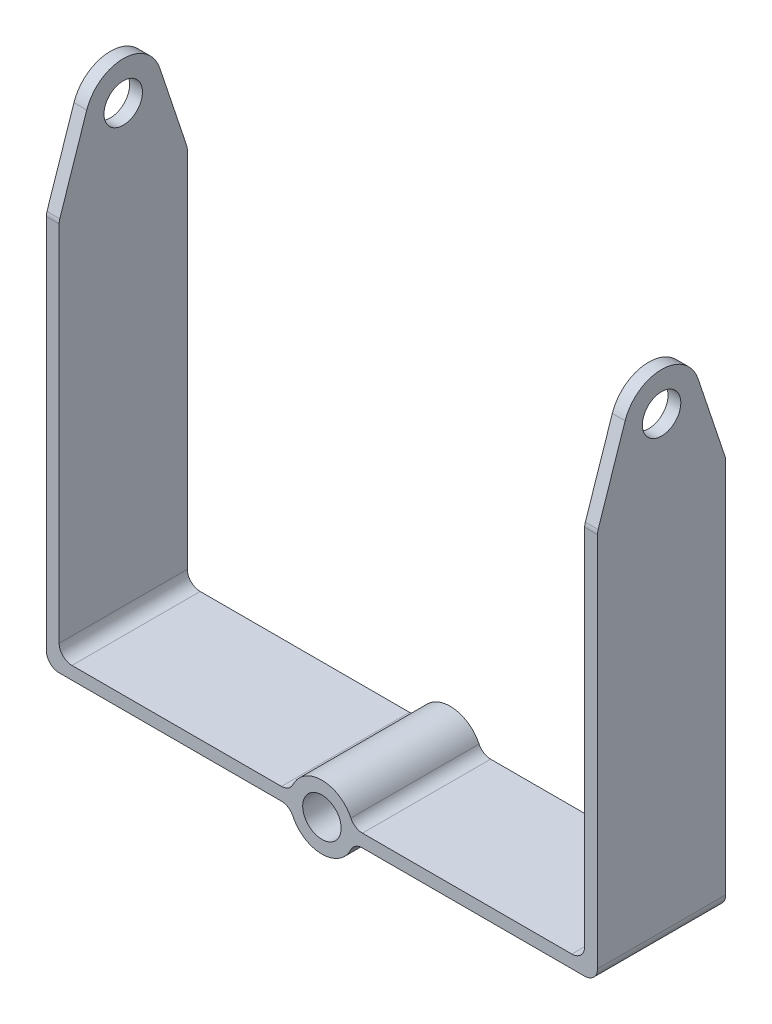
SolidWorks part; units mm, degrees
ref_plane "Plan de face" through (0, 0, 0) normal (0, 0, 1) x (1, 0, 0)
ref_plane "Plan de dessus" through (0, 0, 0) normal (0, 1, 0) x (1, 0, 0)
ref_plane "Plan de droite" through (0, 0, 0) normal (1, 0, 0) x (0, 0, -1)
sketch "Esquisse1" plane through (0, 0, 0) normal (0, 0, 1) x (1, 0, 0)
  line L0 (0, 0) -> (0, 390)
  line L1 (0, 390) -> (10, 390)
  line L2 (10, 390) -> (10, 10)
  line L3 (10, 10) -> (420, 10) construction
  line L4 (420, 10) -> (420, 390)
  line L5 (420, 390) -> (430, 390)
  line L6 (430, 390) -> (430, 0)
  line L7 (0, 0) -> (10, 0)
  line L8 (10, 390) -> (420, 390) construction
  line L9 (420, 10) -> (420, 0) construction
  line L10 (10, 10) -> (10, 0) construction
  line L11 (430, 0) -> (420, 0)
  line L12 (10, 0) -> (420, 0) construction
  line L13 (215, 10) -> (215, 0) construction
  line L14 (190.5051, 10) -> (10, 10)
  line L15 (420, 10) -> (239.4949, 10)
  line L16 (420, 0) -> (239.4949, 0)
  line L17 (10, 0) -> (190.5051, 0)
  circle A0 centre (215, 5) radius 25 construction
  circle A1 centre (215, 5) radius 15
  arc A2 (190.5051, 10) -> (239.4949, 10) centre (215, 5) cw
  arc A3 (190.5051, 0) -> (239.4949, 0) centre (215, 5) ccw
  dimension "D1" = 30
  dimension "D7" = 10
  dimension "D2" = 10
  dimension "D3" = 420
  dimension "D4" = 430
  dimension "D5" = 10
  dimension "D6" = 390
extrude "Boss.-Extru.1" add sketch "Esquisse1" along normal blind 100 contours L17 A3 L16 L11 L6 L5 L4 L15 A2 L14 L2 L1 L0 L7 A1
sketch "Esquisse2" plane through (430, 0, 0) normal (1, 0, 0) x (0, 0, -1)
  line L0 (-50, 390) -> (-50, 30) construction
  line L1 (-100, 390) -> (0, 390) construction
  line L2 (0, 30) -> (-100, 30) construction
  line L3 (-50, 360) -> (-100, 360) construction
  line L4 (-100, 390) -> (-100, 0) construction
  line L5 (-78.4547, 369.5043) -> (-100, 305)
  line L6 (-100, 305) -> (-50, 305) construction
  line L7 (-50, 390) -> (-50, 555.5832) construction
  line L8 (20.947, 555.5832) -> (-120.947, 555.5832)
  line L9 (-120.947, 555.5832) -> (-120.947, 305)
  line L10 (-120.947, 305) -> (-100, 305)
  line L11 (20.947, 305) -> (0, 305)
  line L12 (20.947, 555.5832) -> (20.947, 305)
  line L13 (-21.5453, 369.5043) -> (0, 305)
  line L14 (-100, 0) -> (0, 0) construction
  circle A0 centre (-50, 360) radius 15
  arc A1 (-21.5453, 369.5043) -> (-78.4547, 369.5043) centre (-50, 360) ccw
  point P21 (-50, 390)
  line M1 (-100, 390) -> (-100, 0)
  line M3 (0, 0) -> (0, 390)
  line M4 (0, 390) -> (-100, 390)
  dimension "D1" = 30
  dimension "D2" = 360
  dimension "D3" = 55
extrude "Enlèv. mat.-Extru.1" cut sketch "Esquisse2" against normal through all contours A1 L5 M4 M1 | L12 L8 L9 L10 L11 M1 M4 M3 | A1 L13 M3 M4 | A0
fillet "Congé1" radius 10 12 edges at (10, 10, 50) (0, 0, 50) (239.4949, 0, 50) (190.5051, 0, 50) (190.5051, 10, 50) (239.4949, 10, 50) (420, 10, 50) (430, 0, 50) (425, 305, 0) (425, 305, 100) (5, 305, 100) (5, 305, 0)
